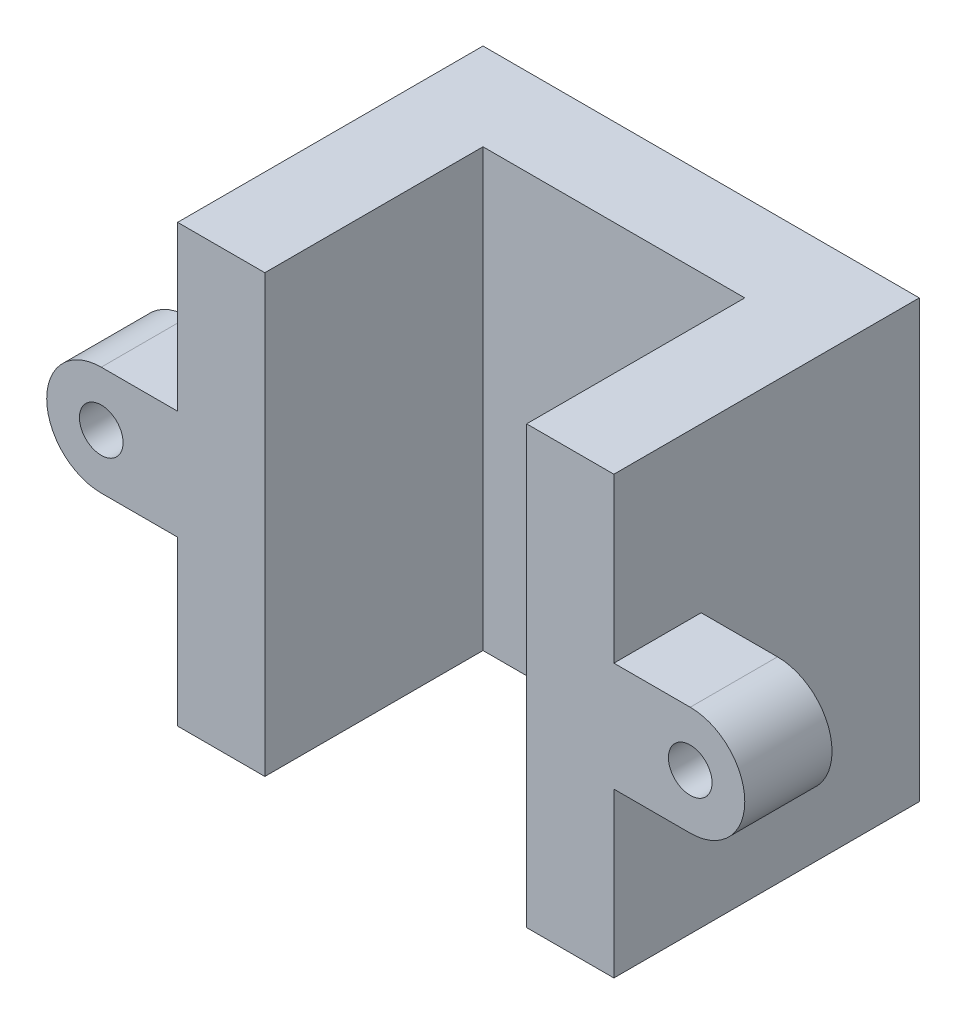
SolidWorks part; units mm, degrees
ref_plane "Front Plane" through (0, 0, 0) normal (0, 0, 1) x (1, 0, 0)
ref_plane "Top Plane" through (0, 0, 0) normal (0, 1, 0) x (1, 0, 0)
ref_plane "Right Plane" through (0, 0, 0) normal (1, 0, 0) x (0, 0, -1)
sketch "Sketch1" plane through (0, 0, 0) normal (0, 1, 0) x (1, 0, 0)
  line L0 (6, -5) -> (10, -5)
  line L2 (-6, -5) -> (-6, 5)
  line L3 (-6, 5) -> (6, 5)
  line L4 (6, -5) -> (6, 5)
  line L5 (-6, -5) -> (6, 5) construction
  line L6 (-6, 5) -> (6, -5) construction
  line L8 (-10, -5) -> (-10, 9)
  line L9 (-10, 9) -> (10, 9)
  line L10 (10, -5) -> (10, 9)
  line L11 (-5.5556, -5) -> (10, 9) construction
  line L12 (-10, 9) -> (5.5556, -5) construction
  line L13 (10, -5) -> (6, -5)
  line L14 (-6, -5) -> (-10, -5)
  point P0 (0, 0)
  point P6 (0, 0)
  dimension "D1" = 12
  dimension "D3" = 20
extrude "Boss-Extrude1" add sketch "Sketch1" along normal blind 20 contours L14 L2 L3 L4 L0 L10 L9 L8
sketch "Sketch2" plane through (10, 0, 0) normal (1, 0, 0) x (0, 0, -1)
  line L0 (-5, 20) -> (-5, 0) construction
  line L1 (-5, 4) -> (-1, 4)
  line L3 (-5, 16) -> (-1, 16)
  line L4 (-1, 4) -> (-1, 16)
  line L5 (-5, 10) -> (-1, 16) construction
  line L6 (-5, 10) -> (-1, 4) construction
  line L7 (-5, 16) -> (-5, 4)
  line L8 (-5, 20) -> (9, 20) construction
  point P0 (-5, 10)
  dimension "D1" = 4
  dimension "D2" = 0
  dimension "D3" = 12
  dimension "D4" = 4
extrude "Boss-Extrude2" add sketch "Sketch2" along normal blind 6
sketch "Sketch3" plane through (0, 0, 1) normal (0, 0, -1) x (-1, 0, 0)
  line L0 (-10, 20) -> (-10, 0) construction
  line L1 (-10, 4) -> (-16, 4)
  line L6 (-16, 16) -> (-10, 16)
  line L7 (-10, 12.5) -> (-10, 7.5)
  line L8 (-16, 16) -> (-16, 4)
  line L9 (-13.5, 12.5) -> (-10, 12.5)
  line L10 (-13.5, 7.5) -> (-10, 7.5)
  line L11 (-16, 4) -> (-10, 4)
  line L12 (-10, 16) -> (-10, 4)
  circle A0 centre (-13.5, 10) radius 1
  arc A1 (-13.5, 12.5) -> (-13.5, 7.5) centre (-13.5, 10) ccw
  point P0 (-10, 10)
  line M1 (-10, 4) -> (-10, 16)
  line M2 (-10, 16) -> (-16, 16)
  line M3 (-16, 16) -> (-16, 4)
  line M4 (-16, 4) -> (-10, 4)
  dimension "D2" = 2
  dimension "D1" = 3.5
extrude "Cut-Extrude1" cut sketch "Sketch3" against normal blind 6 contours A1 L8 L10 M4 M1 | A0 | A1 L9 M1 M2 M3
sketch "Sketch4" plane through (0, 0, 1) normal (0, 0, -1) x (-1, 0, 0)
  line L1 (-13.5, 11.75) -> (-15.0155, 10.875)
  line L2 (-15.0155, 10.875) -> (-15.0155, 9.125)
  line L3 (-15.0155, 9.125) -> (-13.5, 8.25)
  line L4 (-13.5, 8.25) -> (-11.9845, 9.125)
  line L5 (-11.9845, 9.125) -> (-11.9845, 10.875)
  line L6 (-11.9845, 10.875) -> (-13.5, 11.75)
  circle A0 centre (-13.5, 10) radius 1.75 construction
  circle A1 centre (-13.5, 10) radius 1.5155 construction
  dimension "D1" = 3.5
extrude "Cut-Extrude2" cut sketch "Sketch4" against normal blind 2
mirror "Mirror1" about plane through (0, 0, 0) normal (1, 0, 0) of "Cut-Extrude2", "Cut-Extrude1", "Boss-Extrude2"
